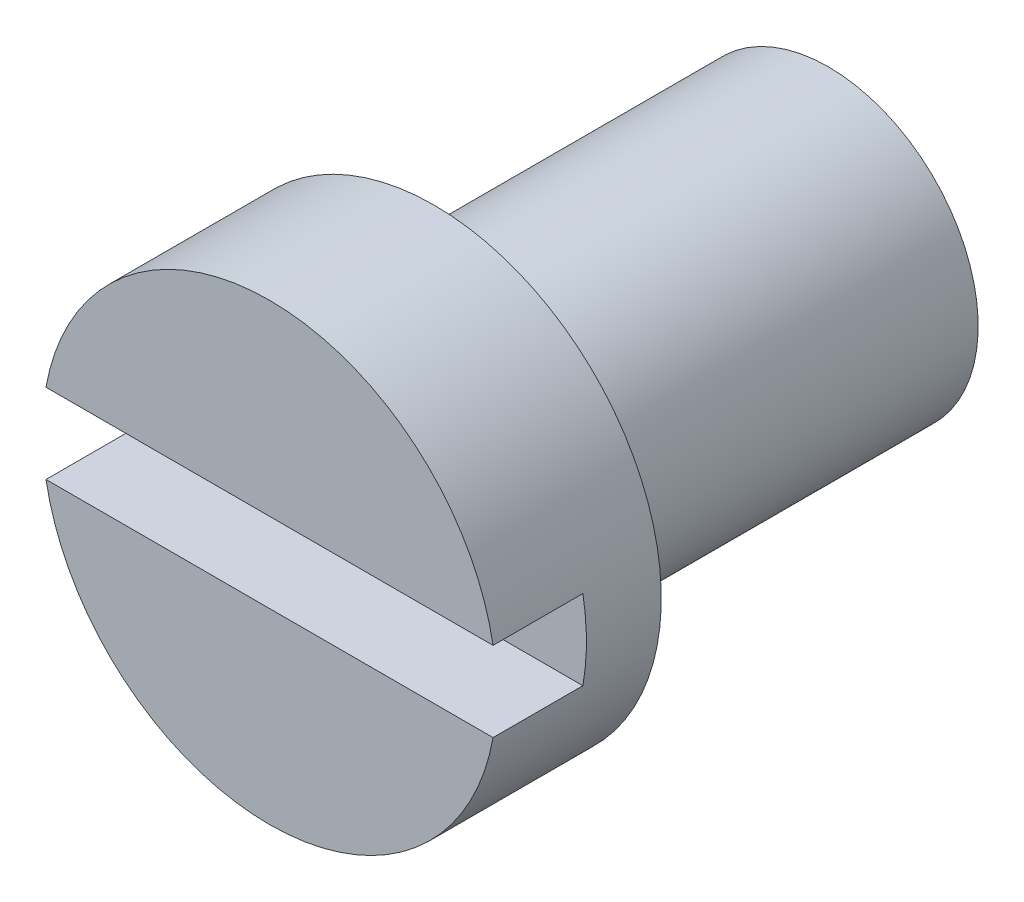
SolidWorks part; units mm, degrees
ref_plane "정면" through (0, 0, 0) normal (0, 0, 1) x (1, 0, 0)
ref_plane "윗면" through (0, 0, 0) normal (0, 1, 0) x (1, 0, 0)
ref_plane "우측면" through (0, 0, 0) normal (1, 0, 0) x (0, 0, -1)
sketch "스케치1" plane through (0, 0, 0) normal (1, 0, 0) x (0, 0, -1)
  line L1 (0, 0) -> (0, 4.55)
  line L2 (0, 4.55) -> (3.3, 4.55)
  line L3 (3.3, 4.55) -> (3.3, 3)
  line L4 (3.3, 3) -> (11.2, 3)
  line L5 (11.2, 3) -> (11.2, 0)
  line L6 (11.2, 0) -> (0, 0)
  dimension "D1" = 11.2
  dimension "D2" = 3.3
  dimension "D3" = 3
  dimension "D4" = 4.55
revolve "회전1" add sketch "스케치1" angle 360 about L6
sketch "스케치2" plane through (0, 0, 0) normal (0, 0, 1) x (1, 0, 0)
  line L1 (-5.8082, 0.8) -> (5.5349, 0.8)
  line L2 (-5.8082, 0.8) -> (-5.8082, -0.8)
  line L3 (-5.8082, -0.8) -> (5.5349, -0.8)
  line L4 (5.5349, 0.8) -> (5.5349, -0.8)
  dimension "D1" = 0.8
  dimension "D2" = 0.8
extrude "컷-돌출1" cut sketch "스케치2" against normal blind 1.8
